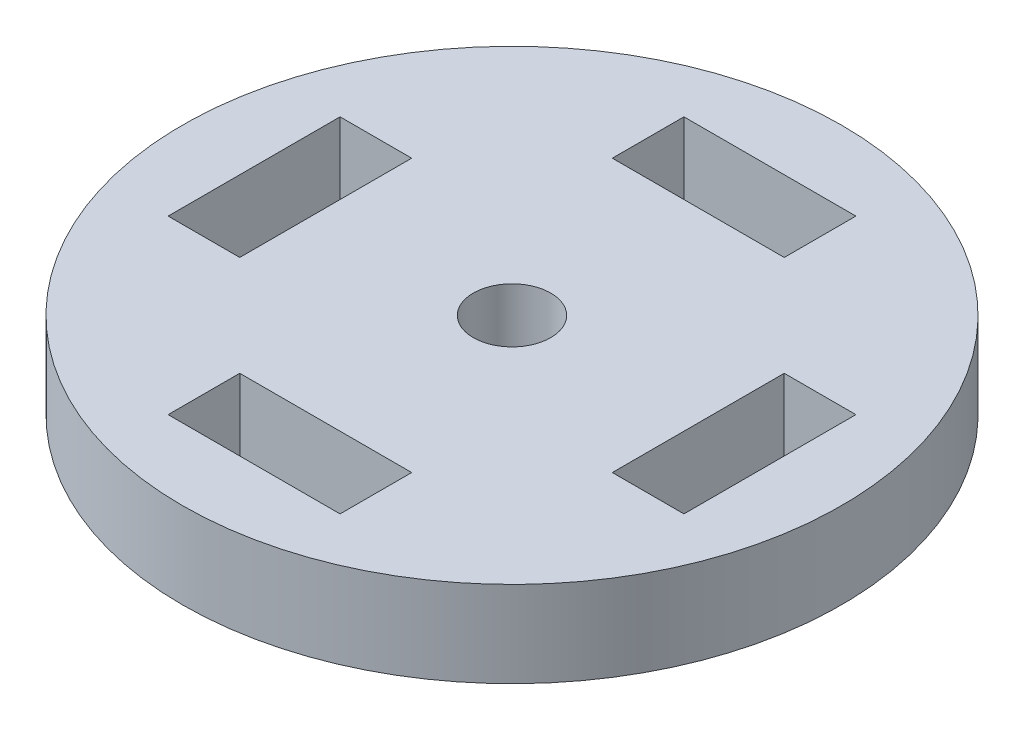
SolidWorks part; units mm, degrees
ref_plane "Front Plane" through (0, 0, 0) normal (0, 0, 1) x (1, 0, 0)
ref_plane "Top Plane" through (0, 0, 0) normal (0, 1, 0) x (1, 0, 0)
ref_plane "Right Plane" through (0, 0, 0) normal (1, 0, 0) x (0, 0, -1)
sketch "Sketch5" plane through (0, 0, 0) normal (0, 1, 0) x (1, 0, 0)
  circle A0 centre (0, 0) radius 11.5
  dimension "D1" = 23
extrude "Boss-Extrude2" add sketch "Sketch5" along normal blind 3
sketch "Sketch3" plane through (0, 0, 0) normal (0, 1, 0) x (1, 0, 0)
  line L0 (0, 0) -> (0, 9) construction
  line L1 (3, 9) -> (-3, 9)
  line L2 (-3, 9) -> (-3, 6.5)
  line L3 (-3, 6.5) -> (3, 6.5)
  line L4 (3, 9) -> (3, 6.5)
  line L5 (0.75, 4.5) -> (-0.75, 4.5) construction
  line L6 (-0.75, 4.5) -> (-0.75, 3) construction
  line L7 (-0.75, 3) -> (0.75, 3) construction
  line L8 (0.75, 4.5) -> (0.75, 3) construction
  line L9 (9, -3) -> (6.5, -3)
  line L10 (6.5, 3) -> (6.5, -3)
  line L11 (9, 3) -> (6.5, 3)
  line L12 (9, -3) -> (9, 3)
  line L17 (-3, -9) -> (-3, -6.5)
  line L18 (3, -6.5) -> (-3, -6.5)
  line L19 (3, -9) -> (3, -6.5)
  line L20 (-3, -9) -> (3, -9)
  line L21 (-0.75, -4.5) -> (-0.75, -3) construction
  line L22 (0.75, -3) -> (-0.75, -3) construction
  line L23 (0.75, -4.5) -> (0.75, -3) construction
  line L24 (-0.75, -4.5) -> (0.75, -4.5) construction
  line L25 (-9, 3) -> (-6.5, 3)
  line L26 (-6.5, -3) -> (-6.5, 3)
  line L27 (-9, -3) -> (-6.5, -3)
  line L28 (-9, 3) -> (-9, -3)
  line L33 (-4.5, 0.75) -> (-3, 0.75) [skipped]
  line L34 (-3, -0.75) -> (-3, 0.75) [skipped]
  line L35 (-4.5, -0.75) -> (-3, -0.75) [skipped]
  line L36 (-4.5, 0.75) -> (-4.5, -0.75) [skipped]
  line L37 (4.5, -0.75) -> (3, -0.75) [skipped]
  line L38 (3, 0.75) -> (3, -0.75) [skipped]
  line L39 (4.5, 0.75) -> (3, 0.75) [skipped]
  line L40 (4.5, -0.75) -> (4.5, 0.75) [skipped]
  point P6 (0, 3)
  point P8 (0, 6.5)
  point P14 (0, 4.5)
  dimension "D1" = 9
  dimension "D2" = 6
  dimension "D3" = 2.5
  dimension "D4" = 1.5
  dimension "D5" = 1.5
  dimension "D6" = 4
extrude "Cut-Extrude1" cut sketch "Sketch3" along normal up to surface (3 mm away) up to face at (0, 3, 11.5)
sketch "Sketch6" plane through (0, 3, 0) normal (0, 1, 0) x (1, 0, 0)
  circle A0 centre (0, 0) radius 1.35
  dimension "D1" = 2.7
extrude "Cut-Extrude2" cut sketch "Sketch6" against normal up to surface (3 mm away) up to face at (7.75, 0, 0)
equation "\"t\"=2.5"
equation "\"h\"= 2.5"
